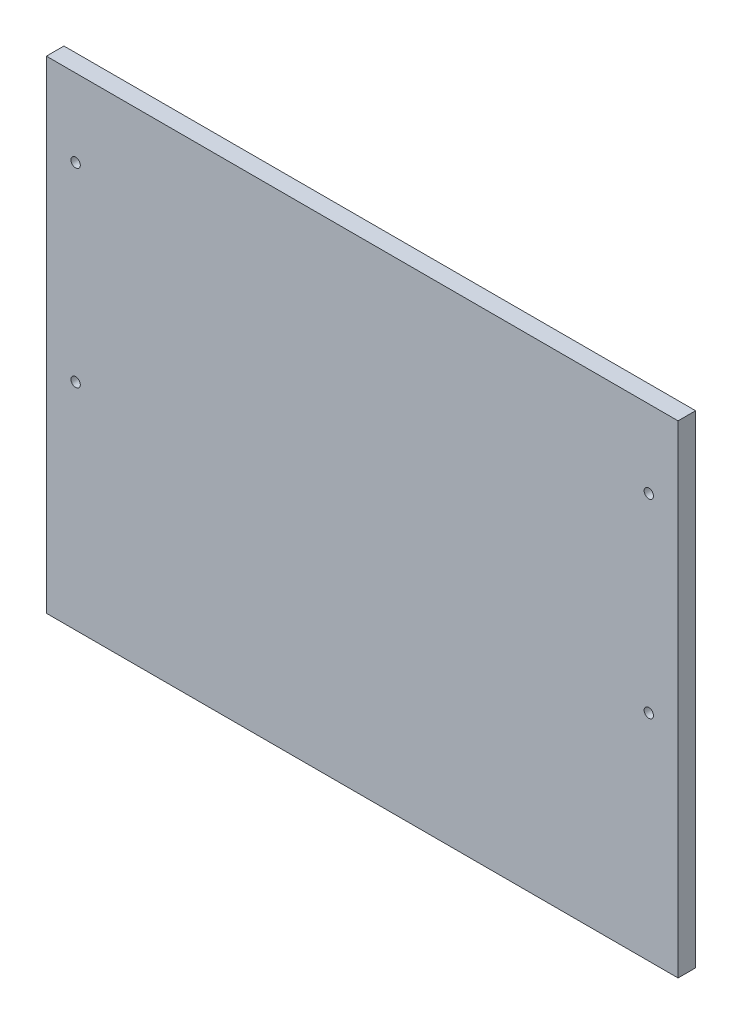
SolidWorks part; units mm, degrees
ref_plane "前视基准面" through (0, 0, 0) normal (0, 0, 1) x (1, 0, 0)
ref_plane "上视基准面" through (0, 0, 0) normal (0, 1, 0) x (1, 0, 0)
ref_plane "右视基准面" through (0, 0, 0) normal (1, 0, 0) x (0, 0, -1)
other "Configuration Table"
sketch "草图1" plane through (0, 0, 0) normal (0, 0, 1) x (1, 0, 0)
  line L0 (0, -235) -> (432, -235)
  line L1 (432, -235) -> (432, 95)
  line L2 (432, 95) -> (0, 95)
  line L3 (0, 95) -> (0, -235)
  circle A0 centre (20, 42) radius 3.2
  circle A1 centre (412, 42) radius 3.2
  circle A2 centre (20, -88) radius 3.2
  circle A3 centre (412, -88) radius 3.2
extrude "凸台-拉伸1" add sketch "草图1" along normal blind 12
